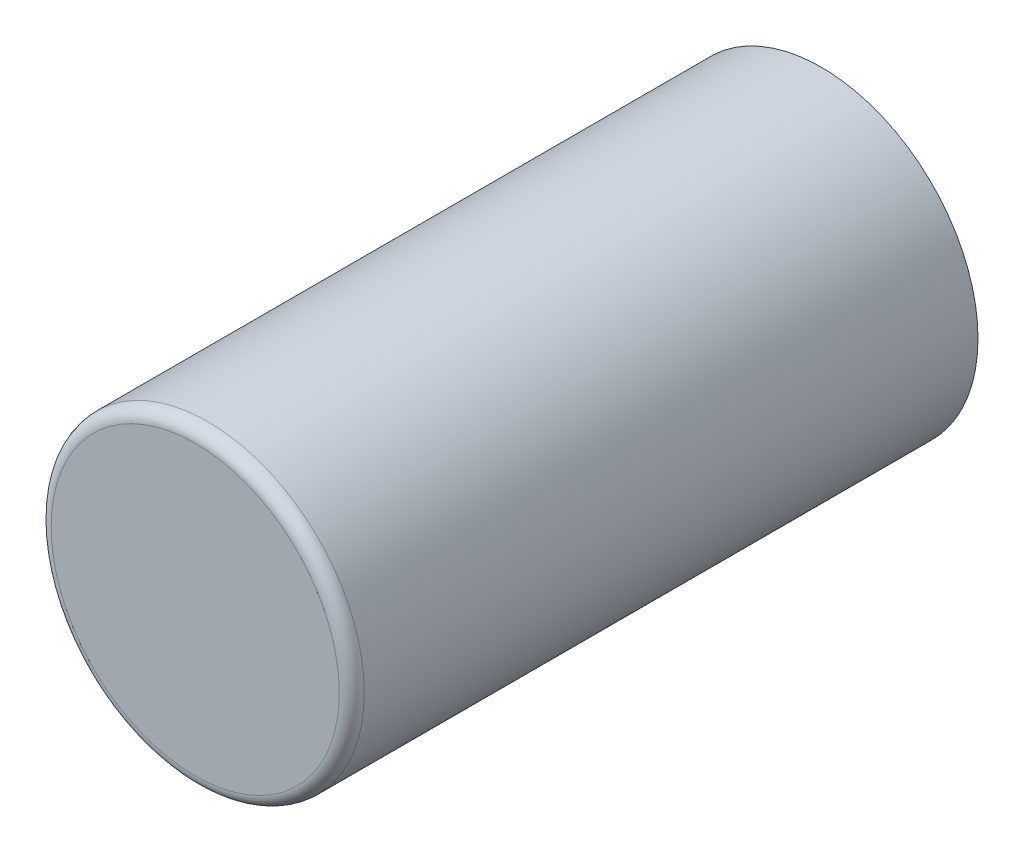
SolidWorks part; units mm, degrees
ref_plane "Спереди" through (0, 0, 0) normal (0, 0, 1) x (1, 0, 0)
ref_plane "Сверху" through (0, 0, 0) normal (0, 1, 0) x (1, 0, 0)
ref_plane "Справа" through (0, 0, 0) normal (1, 0, 0) x (0, 0, -1)
sketch "Эскиз1" plane through (0, 0, 0) normal (0, 0, 1) x (1, 0, 0)
  circle A0 centre (0, 0) radius 25
  dimension "D1" = 50
extrude "Бобышка-Вытянуть1" add sketch "Эскиз1" along normal blind 100
fillet "Скругление1" radius 2 1 edges at (25, 0, 100)
